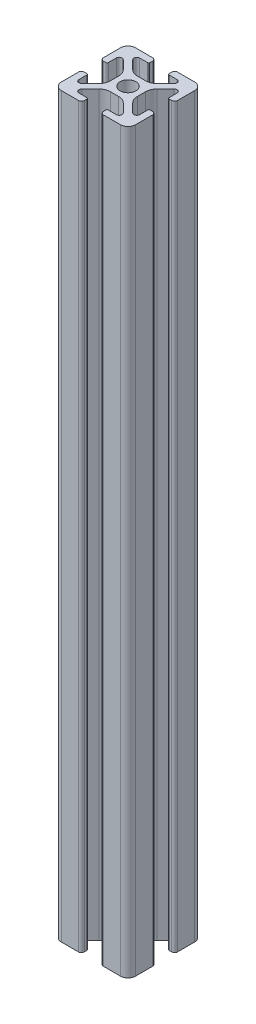
SolidWorks part; units mm, degrees
ref_plane "Front Plane" through (0, 0, 0) normal (0, 0, 1) x (1, 0, 0)
ref_plane "Top Plane" through (0, 0, 0) normal (0, 1, 0) x (1, 0, 0)
ref_plane "Right Plane" through (0, 0, 0) normal (1, 0, 0) x (0, 0, -1)
ref_plane "Plane1" through (0, 0, 0) normal (0, -1, 0) x (1, 0, 0)
sketch "Sketch1" plane through (0, 0, 0) normal (0, -1, 0) x (1, 0, 0)
  line L0 (-3.375, 10) -> (-8, 10)
  line L1 (-10, 8) -> (-10, 3.375)
  line L2 (-9.2, 2.575) -> (-8.5, 2.575)
  line L3 (-8.2, 2.875) -> (-8.2, 5.0441)
  line L4 (-6.8685, 5.5957) -> (-4.5287, 3.2559)
  line L5 (-3.65, 1.1346) -> (-3.65, -1.1346)
  line L6 (-4.5287, -3.2559) -> (-6.8685, -5.5957)
  line L7 (-8.2, -5.0441) -> (-8.2, -2.875)
  line L8 (-8.5, -2.575) -> (-9.2, -2.575)
  line L9 (-10, -3.375) -> (-10, -8)
  line L10 (-8, -10) -> (-3.375, -10)
  line L11 (-2.5629, -9.1879) -> (-2.5629, -8.4252)
  line L12 (-2.8002, -8.1879) -> (-5.0491, -8.1879)
  line L13 (-5.5957, -6.8685) -> (-3.2559, -4.5287)
  line L14 (-1.1346, -3.65) -> (1.1346, -3.65)
  line L15 (3.2559, -4.5287) -> (5.5957, -6.8685)
  line L16 (5.0491, -8.1879) -> (2.8871, -8.1879)
  line L17 (2.575, -8.5) -> (2.575, -9.2)
  line L18 (3.375, -10) -> (8, -10)
  line L19 (10, -8) -> (10, -3.375)
  line L20 (9.2, -2.575) -> (8.5, -2.575)
  line L21 (8.2, -2.875) -> (8.2, -5.0441)
  line L22 (6.8685, -5.5957) -> (4.5287, -3.2559)
  line L23 (3.65, -1.1346) -> (3.65, 1.1346)
  line L24 (4.5287, 3.2559) -> (6.8685, 5.5957)
  line L25 (8.2, 5.0441) -> (8.2, 2.875)
  line L26 (8.5, 2.575) -> (9.2, 2.575)
  line L27 (10, 3.375) -> (10, 8)
  line L28 (8, 10) -> (3.375, 10)
  line L29 (2.575, 9.2) -> (2.575, 8.5)
  line L30 (2.875, 8.2) -> (5.0441, 8.2)
  line L31 (5.5957, 6.8685) -> (3.2559, 4.5287)
  line L32 (1.1346, 3.65) -> (-1.1346, 3.65)
  line L33 (-3.2559, 4.5287) -> (-5.5957, 6.8685)
  line L34 (-5.0441, 8.2) -> (-2.875, 8.2)
  line L35 (-2.5629, 8.5121) -> (-2.5629, 9.1879)
  circle A0 centre (0, 0) radius 2.15
  arc A1 (-8, 10) -> (-10, 8) centre (-8, 8) ccw
  arc A2 (-10, 3.375) -> (-9.2, 2.575) centre (-9.2, 3.375) ccw
  arc A3 (-8.5, 2.575) -> (-8.2, 2.875) centre (-8.5, 2.875) ccw
  arc A4 (-8.2, 5.0441) -> (-6.8685, 5.5957) centre (-7.42, 5.0441) cw
  arc A5 (-4.5287, 3.2559) -> (-3.65, 1.1346) centre (-6.65, 1.1346) cw
  arc A6 (-3.65, -1.1346) -> (-4.5287, -3.2559) centre (-6.65, -1.1346) cw
  arc A7 (-6.8685, -5.5957) -> (-8.2, -5.0441) centre (-7.42, -5.0441) cw
  arc A8 (-8.2, -2.875) -> (-8.5, -2.575) centre (-8.5, -2.875) ccw
  arc A9 (-9.2, -2.575) -> (-10, -3.375) centre (-9.2, -3.375) ccw
  arc A10 (-10, -8) -> (-8, -10) centre (-8, -8) ccw
  arc A11 (-3.375, -10) -> (-2.5629, -9.1879) centre (-3.375, -9.1879) ccw
  arc A12 (-2.5629, -8.4252) -> (-2.8002, -8.1879) centre (-2.8002, -8.4252) ccw
  arc A13 (-5.0491, -8.1879) -> (-5.5957, -6.8685) centre (-5.0491, -7.415) cw
  arc A14 (-3.2559, -4.5287) -> (-1.1346, -3.65) centre (-1.1346, -6.65) cw
  arc A15 (1.1346, -3.65) -> (3.2559, -4.5287) centre (1.1346, -6.65) cw
  arc A16 (5.5957, -6.8685) -> (5.0491, -8.1879) centre (5.0491, -7.415) cw
  arc A17 (2.8871, -8.1879) -> (2.575, -8.5) centre (2.8871, -8.5) ccw
  arc A18 (2.575, -9.2) -> (3.375, -10) centre (3.375, -9.2) ccw
  arc A19 (8, -10) -> (10, -8) centre (8, -8) ccw
  arc A20 (10, -3.375) -> (9.2, -2.575) centre (9.2, -3.375) ccw
  arc A21 (8.5, -2.575) -> (8.2, -2.875) centre (8.5, -2.875) ccw
  arc A22 (8.2, -5.0441) -> (6.8685, -5.5957) centre (7.42, -5.0441) cw
  arc A23 (4.5287, -3.2559) -> (3.65, -1.1346) centre (6.65, -1.1346) cw
  arc A24 (3.65, 1.1346) -> (4.5287, 3.2559) centre (6.65, 1.1346) cw
  arc A25 (6.8685, 5.5957) -> (8.2, 5.0441) centre (7.42, 5.0441) cw
  arc A26 (8.2, 2.875) -> (8.5, 2.575) centre (8.5, 2.875) ccw
  arc A27 (9.2, 2.575) -> (10, 3.375) centre (9.2, 3.375) ccw
  arc A28 (10, 8) -> (8, 10) centre (8, 8) ccw
  arc A29 (3.375, 10) -> (2.575, 9.2) centre (3.375, 9.2) ccw
  arc A30 (2.575, 8.5) -> (2.875, 8.2) centre (2.875, 8.5) ccw
  arc A31 (5.0441, 8.2) -> (5.5957, 6.8685) centre (5.0441, 7.42) cw
  arc A32 (3.2559, 4.5287) -> (1.1346, 3.65) centre (1.1346, 6.65) cw
  arc A33 (-1.1346, 3.65) -> (-3.2559, 4.5287) centre (-1.1346, 6.65) cw
  arc A34 (-5.5957, 6.8685) -> (-5.0441, 8.2) centre (-5.0441, 7.42) cw
  arc A35 (-2.875, 8.2) -> (-2.5629, 8.5121) centre (-2.875, 8.5121) ccw
  arc A36 (-2.5629, 9.1879) -> (-3.375, 10) centre (-3.375, 9.1879) ccw
extrude "Boss-Extrude1" add sketch "Sketch1" against normal blind 199
